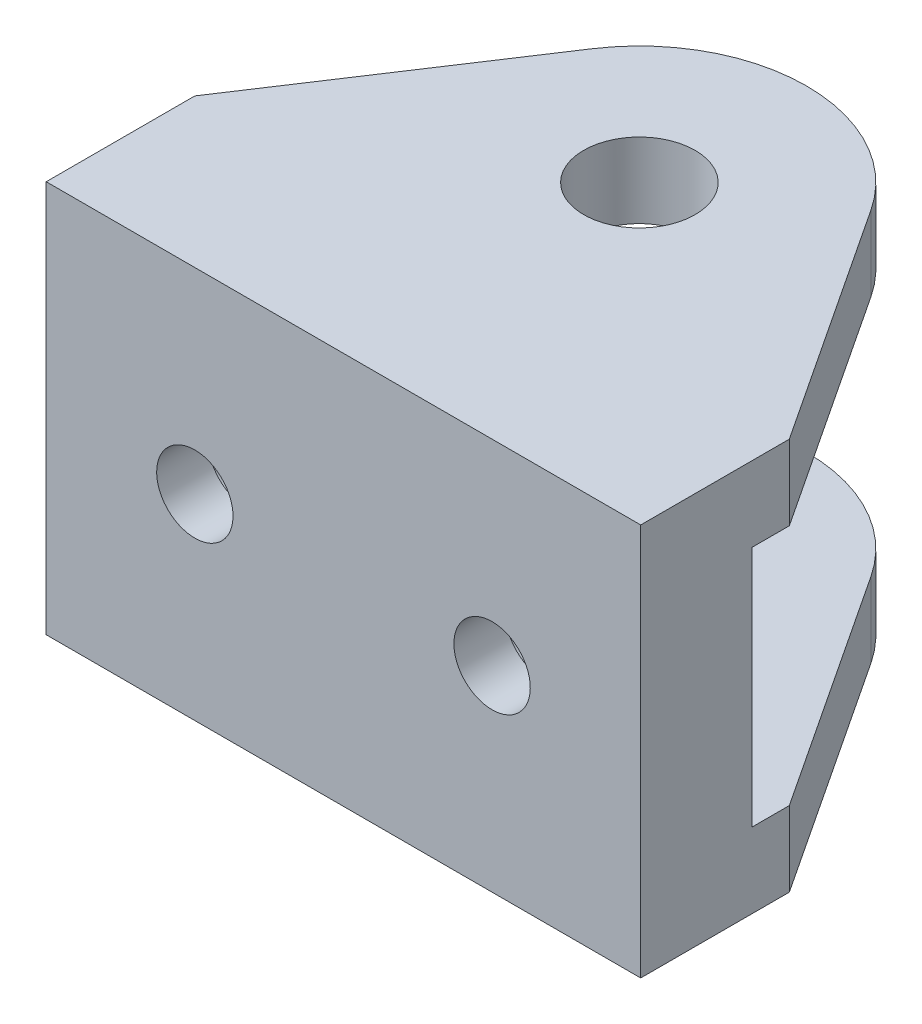
SolidWorks part; units mm, degrees
material "6061-T6 (SS)"
ref_plane "Front Plane" through (0, 0, 0) normal (0, 0, 1) x (1, 0, 0)
ref_plane "Top Plane" through (0, 0, 0) normal (0, 1, 0) x (1, 0, 0)
ref_plane "Right Plane" through (0, 0, 0) normal (1, 0, 0) x (0, 0, -1)
sketch "Sketch1" plane through (0, 0, 0) normal (1, 0, 0) x (0, 0, -1)
  line L0 (41.7969, 27.1145) -> (9.4996, 27.1145)
  line L1 (0, 0) -> (41.7969, 0)
  line L2 (0, 0) -> (0, 33.528)
  line L3 (0, 33.528) -> (41.7969, 33.528)
  line L4 (41.7969, 0) -> (41.7969, 6.4135)
  line L5 (9.4996, 27.1145) -> (9.4996, 6.4135)
  line L6 (9.4996, 6.4135) -> (41.7969, 6.4135)
  line L7 (41.7969, 27.1145) -> (41.7969, 33.528)
  line L8 (25.2869, 33.528) -> (25.2869, 0) construction
  dimension "D2" = 33.528
  dimension "D3" = 20.701
  dimension "D4" = 9.4996
  dimension "D5" = 16.51
extrude "Boss-Extrude1" add sketch "Sketch1" along normal blind 50.8
sketch "Sketch2" plane through (0, 0, -9.4996) normal (0, 0, -1) x (-1, 0, 0)
  line L0 (-25.4, 27.1145) -> (-25.4, 6.4135) construction
  line L1 (-50.8, 27.1145) -> (0, 27.1145) construction
  line L2 (-50.8, 6.4135) -> (0, 6.4135) construction
  line L3 (-38.1, 16.764) -> (-12.7, 16.764) construction
  circle A0 centre (-38.1, 16.764) radius 3.2639
  circle A1 centre (-12.7, 16.764) radius 3.2639
  point P8 (-25.4, 16.764)
  dimension "D2" = 6.5278
  dimension "D1" = 25.4
extrude "1/4 Clearnace Holes" cut sketch "Sketch2" against normal up to surface (9.4996 mm away) up to face at (25.4, 16.764, 0)
sketch "Sketch3" plane through (0, 0, 0) normal (0, -1, 0) x (1, 0, 0)
  line L0 (0, -12.7) -> (13.4685, -33.1464)
  line L1 (0, 0) -> (0, -41.7969) construction
  line L2 (37.3315, -33.1464) -> (50.8, -12.7)
  line L3 (50.8, 0) -> (50.8, -41.7969) construction
  line L4 (50.8, 0) -> (0, 0) construction
  line L6 (0, -12.7) -> (0, -41.7969)
  line L7 (0, -41.7969) -> (50.8, -41.7969)
  line L8 (50.8, -41.7969) -> (50.8, -12.7)
  arc A0 (13.4685, -33.1464) -> (37.3315, -33.1464) centre (25.4, -25.2869) ccw
  circle A1 centre (25.4, -25.2869) radius 4.7625
  dimension "D3" = 9.525
  dimension "D4" = 9.525
  dimension "D1" = 12.7
  dimension "D2" = 12.7
extrude "Cut-Extrude2" cut sketch "Sketch3" against normal up to surface (33.528 mm away) up to face at (25.4, 33.528, -20.8985)
sketch "Sketch4" plane through (0, 0, -9.4996) normal (0, 0, -1) x (-1, 0, 0)
  circle A0 centre (-12.7, 16.764) radius 4.7625
  circle A1 centre (-38.1, 16.764) radius 4.7625
  dimension "D1" = 9.525
extrude "3/8 Head" cut sketch "Sketch4" against normal blind 5.08
equation "\"1inch\"=62.1211"
